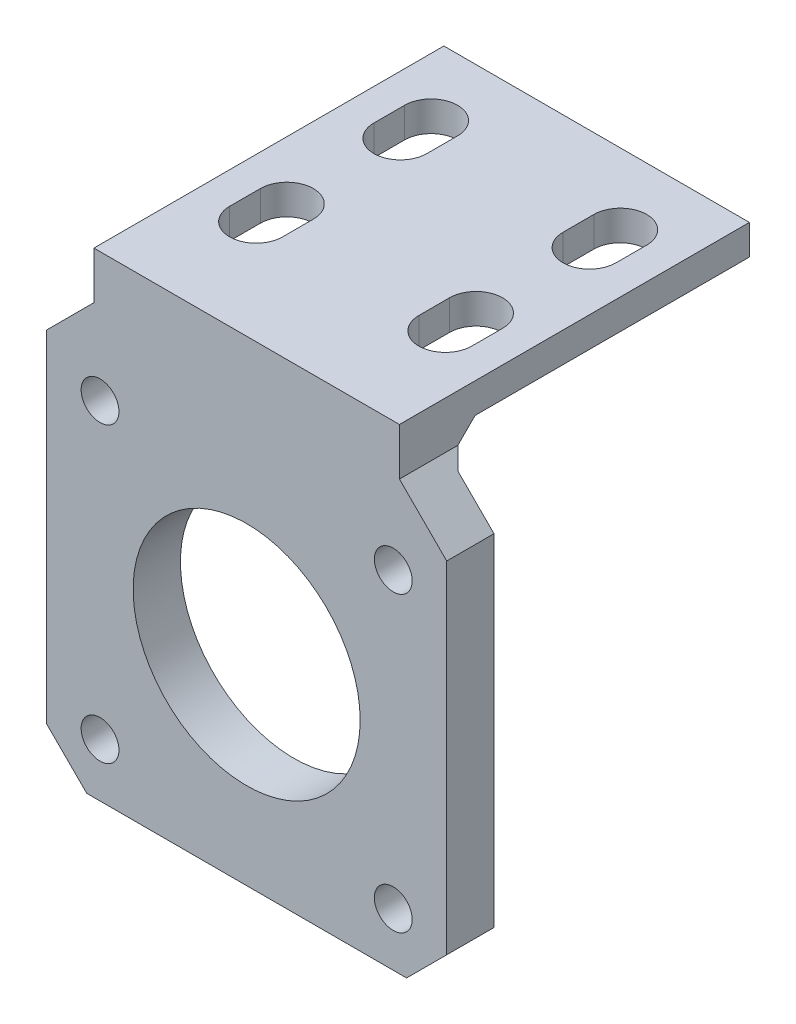
SolidWorks part; units mm, degrees
ref_plane "Front Plane" through (0, 0, 0) normal (0, 0, 1) x (1, 0, 0)
ref_plane "Top Plane" through (0, 0, 0) normal (0, 1, 0) x (1, 0, 0)
ref_plane "Right Plane" through (0, 0, 0) normal (1, 0, 0) x (0, 0, -1)
sketch "Sketch1" plane through (0, 0, 0) normal (0, 0, 1) x (1, 0, 0)
  line L0 (-21.15, -14.15) -> (-21.15, 14.15) construction
  line L2 (14.15, -21.15) -> (-14.15, -21.15) construction
  line L4 (21.15, 14.15) -> (21.15, -14.15) construction
  line L5 (-21.15, -16.9074) -> (-21.15, 24.15)
  line L6 (-16.9074, -21.15) -> (-21.15, -16.9074)
  line L7 (16.9074, -21.15) -> (-16.9074, -21.15)
  line L8 (21.15, -16.9074) -> (16.9074, -21.15)
  line L9 (21.15, 24.15) -> (21.15, -16.9074)
  line L10 (21.15, 24.15) -> (16.15, 24.15)
  line L11 (16.15, 24.15) -> (-16.15, 24.15) construction
  line L12 (-16.15, 24.15) -> (-21.15, 24.15)
  line L13 (-16.15, 24.15) -> (-16.15, 29.15)
  line L14 (-20, 29.15) -> (-10.3, 29.15) construction
  line L15 (-16.15, 29.15) -> (16.15, 29.15)
  line L16 (13.3, 29.15) -> (20, 29.15) construction
  line L17 (16.15, 29.15) -> (16.15, 24.15)
  circle A0 centre (-15.5, 15.5) radius 1.5 construction
  circle A1 centre (15.5, 15.5) radius 1.5 construction
  circle A2 centre (15.5, -15.5) radius 1.5 construction
  circle A3 centre (-15.5, -15.5) radius 1.5 construction
  circle A4 centre (-15.5, 15.5) radius 1.5 construction
  circle A5 centre (15.5, 15.5) radius 1.5 construction
  circle A6 centre (15.5, -15.5) radius 1.5 construction
  circle A7 centre (-15.5, -15.5) radius 1.5 construction
  circle A8 centre (-15.5, 15.5) radius 2
  circle A9 centre (-15.5, -15.5) radius 2
  circle A10 centre (0, 0) radius 12
  circle A11 centre (0, 0) radius 12
  circle A12 centre (15.5, -15.5) radius 2
  circle A13 centre (15.5, 15.5) radius 2
  dimension "D7" = 4
  dimension "D2" = 5
  dimension "D3" = 5
  dimension "D4" = 6
  dimension "D5" = 135
  dimension "D6" = 135
  dimension "D1" = 1
extrude "Boss-Extrude1" add sketch "Sketch1" along normal blind 5
sketch "Sketch2" plane through (0, 0, 0) normal (0, 0, -1) x (-1, 0, 0)
  line L0 (-16.15, 24.15) -> (-16.15, 29.15) construction
  line L1 (16.15, 29.15) -> (-16.15, 29.15)
  line L2 (16.15, 29.15) -> (16.15, 25.975)
  line L3 (16.15, 25.975) -> (-16.15, 25.975)
  line L4 (-16.15, 29.15) -> (-16.15, 25.975)
  dimension "D1" = 3.175
extrude "Boss-Extrude2" add sketch "Sketch2" along normal blind 32
chamfer "Chamfer1" distance 3 angle 45 1 edges
sketch "Sketch3" plane through (0, 25.975, 0) normal (0, -1, 0) x (1, 0, 0)
  line L0 (10, 212) -> (10, -38) construction
  line L1 (-10, 212) -> (-10, -38) construction
  line L2 (10, 212) -> (10, -38) construction
  line L3 (-10, 212) -> (-10, -38) construction
  line L4 (10, -9.25) -> (10, -6) construction
  line L5 (7.2, -9.25) -> (7.2, -6)
  line L6 (12.8, -9.25) -> (12.8, -6)
  line L7 (-10, -9.25) -> (-10, -6) construction
  line L8 (-12.8, -9.25) -> (-12.8, -6)
  line L9 (-7.2, -9.25) -> (-7.2, -6)
  line L10 (-10, -6) -> (10, -6) construction
  line L11 (-10, -9.25) -> (10, -9.25) construction
  line L12 (10, -21.25) -> (10, -24.5) construction
  line L13 (12.8, -21.25) -> (12.8, -24.5)
  line L14 (7.2, -21.25) -> (7.2, -24.5)
  line L15 (-10, -21.25) -> (-10, -24.5) construction
  line L16 (-7.2, -21.25) -> (-7.2, -24.5)
  line L17 (-12.8, -21.25) -> (-12.8, -24.5)
  line L18 (-10, -21.25) -> (10, -21.25) construction
  line L19 (16.15, -32) -> (-16.15, -32) construction
  line L20 (16.15, -3) -> (-16.15, -3) construction
  arc A0 (7.2, -9.25) -> (12.8, -9.25) centre (10, -9.25) ccw
  arc A1 (12.8, -6) -> (7.2, -6) centre (10, -6) ccw
  arc A2 (-12.8, -9.25) -> (-7.2, -9.25) centre (-10, -9.25) ccw
  arc A3 (-7.2, -6) -> (-12.8, -6) centre (-10, -6) ccw
  arc A4 (12.8, -21.25) -> (7.2, -21.25) centre (10, -21.25) ccw
  arc A5 (7.2, -24.5) -> (12.8, -24.5) centre (10, -24.5) ccw
  arc A6 (-7.2, -21.25) -> (-12.8, -21.25) centre (-10, -21.25) ccw
  arc A7 (-12.8, -24.5) -> (-7.2, -24.5) centre (-10, -24.5) ccw
  point P6 (10, -7.625)
  point P11 (-10, -7.625)
  point P24 (10, -22.875)
  point P29 (-10, -22.875)
  dimension "D1" = 2.8
  dimension "D2" = 7.5
  dimension "D3" = 12
  dimension "D4" = 3
extrude "Cut-Extrude1" cut sketch "Sketch3" against normal blind 10
sketch "Sketch4" plane through (0, 0, 5) normal (0, 0, 1) x (1, 0, 0)
  line L0 (16.15, 24.15) -> (21.15, 19.15)
  line L1 (21.15, -16.9074) -> (21.15, 24.15) construction
  line L2 (21.15, 19.15) -> (21.15, 24.15)
  line L3 (21.15, 24.15) -> (16.15, 24.15)
  line L4 (-21.15, 24.15) -> (-16.15, 24.15)
  line L5 (-16.15, 24.15) -> (-21.15, 19.15)
  line L6 (-21.15, 24.15) -> (-21.15, -16.9074) construction
  line L7 (-21.15, 19.15) -> (-21.15, 24.15)
extrude "Cut-Extrude2" cut sketch "Sketch4" against normal blind 10
sketch "Sketch5" plane through (0, 0, -32) normal (0, 0, -1) x (-1, 0, 0)
  line L0 (-16.15, 25.975) -> (16.15, 25.975) construction
  line L1 (4.6096, 28.3179) -> (-4.6096, 28.3179)
  line L2 (4.6096, 28.3179) -> (4.6096, 23.6321)
  line L3 (4.6096, 23.6321) -> (-4.6096, 23.6321)
  line L4 (-4.6096, 28.3179) -> (-4.6096, 23.6321)
  line L5 (4.6096, 28.3179) -> (-4.6096, 23.6321) construction
  line L6 (4.6096, 23.6321) -> (-4.6096, 28.3179) construction
  point P0 (0, 25.975)
extrude "Boss-Extrude3" add sketch "Sketch5" against normal up to next
